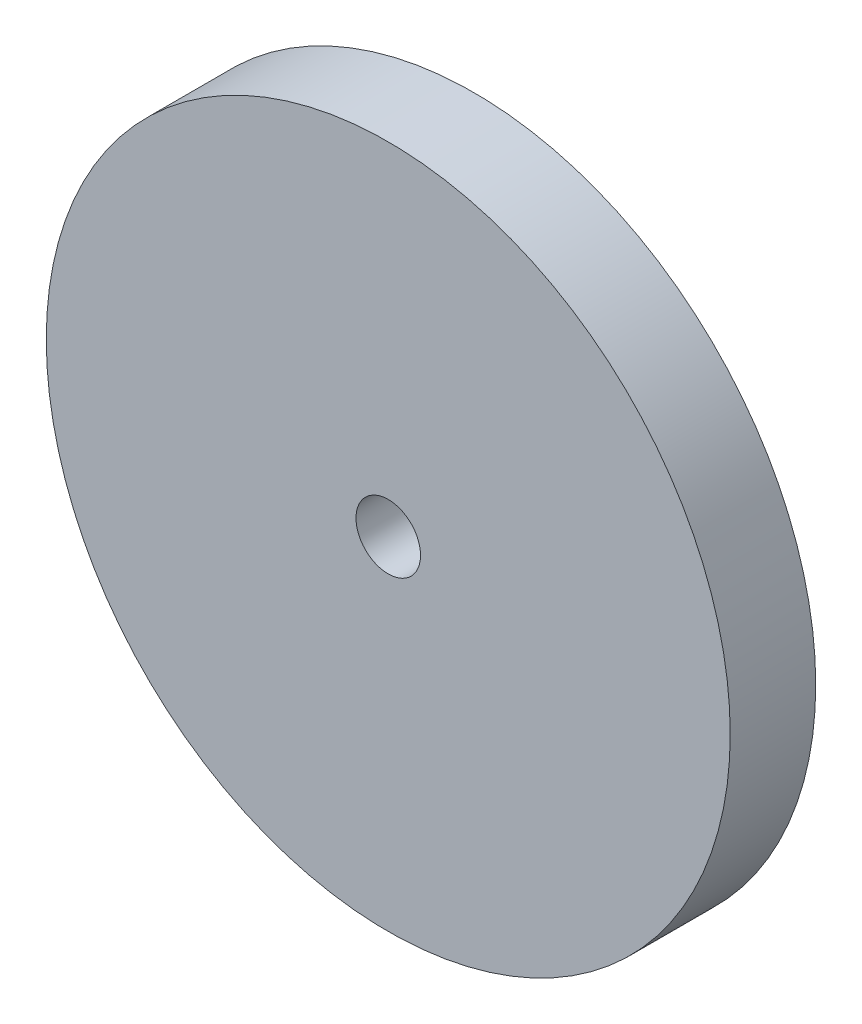
SolidWorks part; units mm, degrees
ref_plane "Front Plane" through (0, 0, 0) normal (0, 0, 1) x (1, 0, 0)
ref_plane "Top Plane" through (0, 0, 0) normal (0, 1, 0) x (1, 0, 0)
ref_plane "Right Plane" through (0, 0, 0) normal (1, 0, 0) x (0, 0, -1)
sketch "Sketch1" plane through (0, 0, 0) normal (0, 0, 1) x (1, 0, 0)
  circle A0 centre (0, 0) radius 3.775
  circle A1 centre (0, 0) radius 40
  dimension "D1" = 80
  dimension "D2" = 7.55
extrude "Boss-Extrude1" add sketch "Sketch1" along normal blind 10
